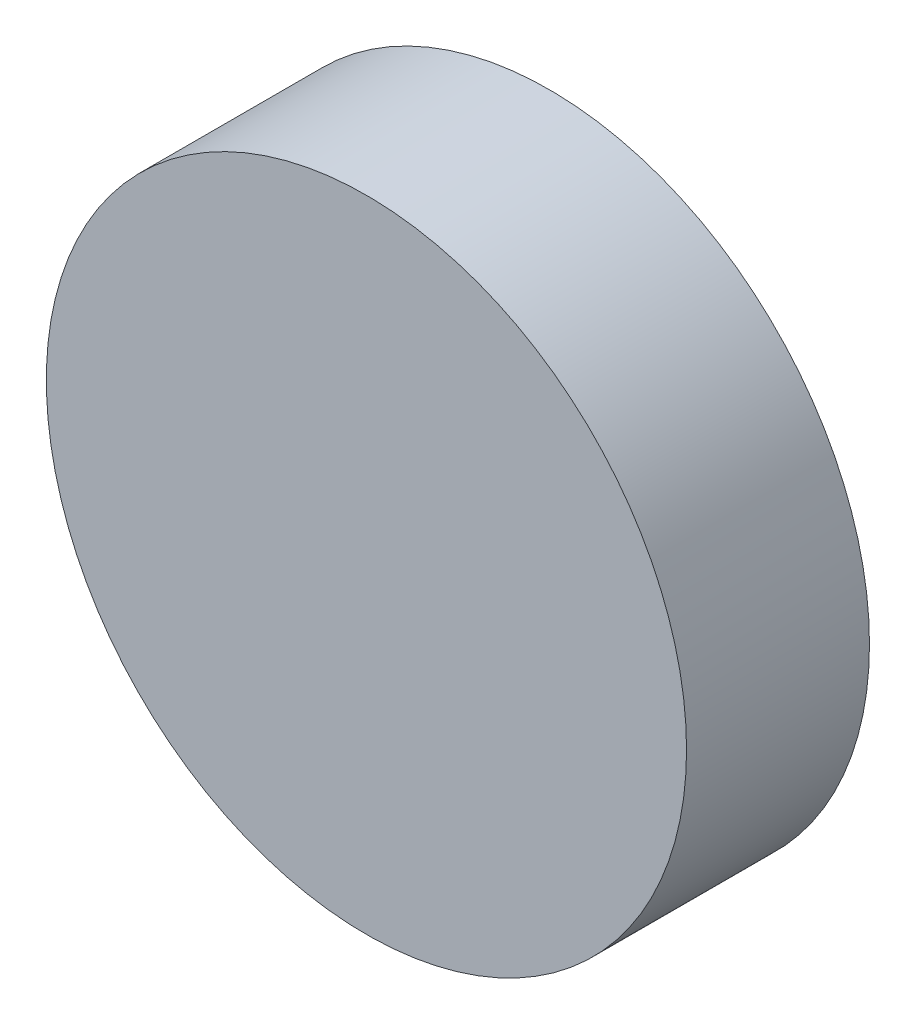
SolidWorks part; units mm, degrees
ref_plane "Front Plane" through (0, 0, 0) normal (0, 0, 1) x (1, 0, 0)
ref_plane "Top Plane" through (0, 0, 0) normal (0, 1, 0) x (1, 0, 0)
ref_plane "Right Plane" through (0, 0, 0) normal (1, 0, 0) x (0, 0, -1)
other "Configuration Table"
sketch "Sketch1" plane through (0, 0, 0) normal (0, 0, 1) x (1, 0, 0)
  circle A0 centre (450, 105) radius 70
extrude "TOPPING_sog_kondenser_fan_D140" add sketch "Sketch1" against normal blind 40 from offset 200 separate body
